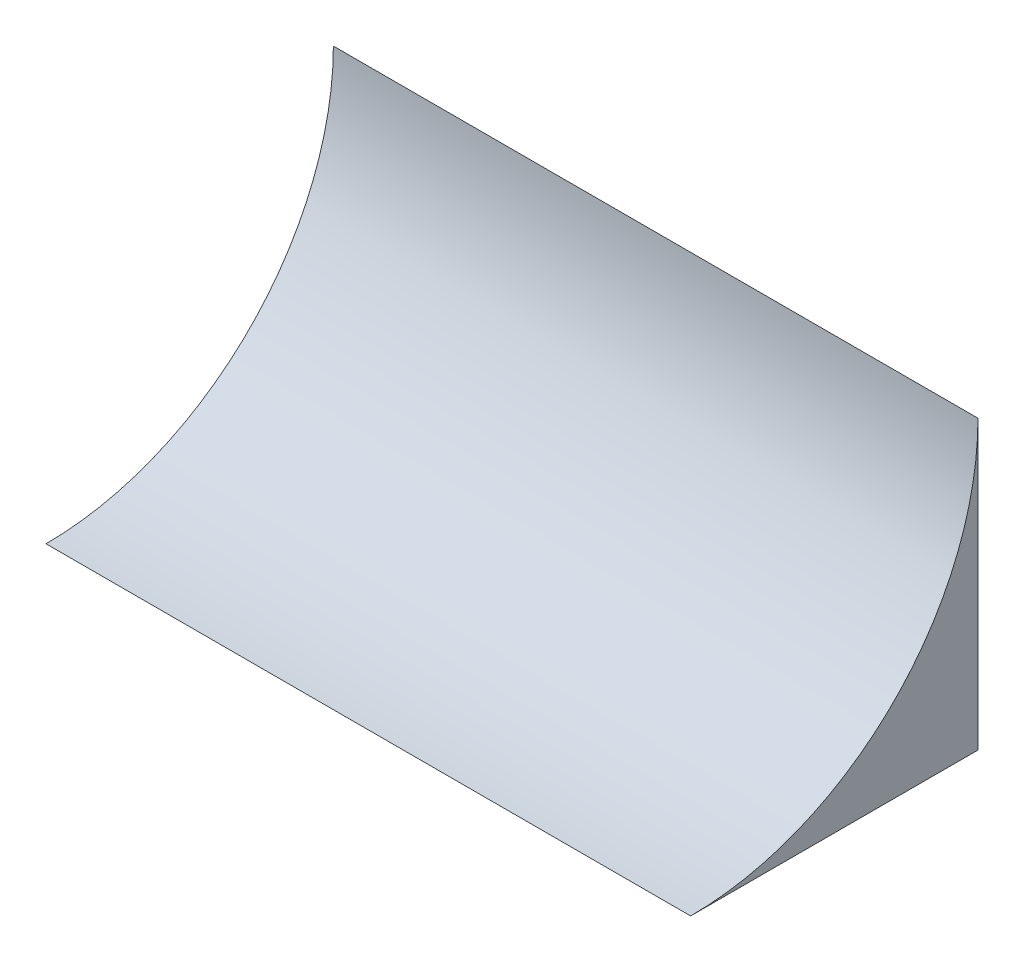
SolidWorks part; units mm, degrees
ref_plane "Front Plane" through (0, 0, 0) normal (0, 0, 1) x (1, 0, 0)
ref_plane "Top Plane" through (0, 0, 0) normal (0, 1, 0) x (1, 0, 0)
ref_plane "Right Plane" through (0, 0, 0) normal (1, 0, 0) x (0, 0, -1)
sketch "Sketch1" plane through (0, 0, 0) normal (1, 0, 0) x (0, 0, -1)
  line L6 (-22.29, -22.29) -> (22.29, -22.29)
  line L8 (-22.29, -22.29) -> (-22.29, 22.29)
  line L9 (-22.29, 22.29) -> (22.29, 22.29)
  line L10 (22.29, -22.29) -> (22.29, 22.29)
  line L11 (0, 22.29) -> (0, -22.29) construction
  line L12 (-22.29, 0) -> (22.29, 0) construction
  point P0 (0, 0)
  point P1 (0, 0)
  dimension "D1" = 44.58
  dimension "D2" = 44.58
extrude "Boss-Extrude1" add sketch "Sketch1" along normal blind 100
sketch "Sketch2" plane through (100, 0, 0) normal (1, 0, 0) x (0, 0, -1)
  circle A0 centre (-22.29, 22.29) radius 44.58
extrude "Cut-Extrude1" cut sketch "Sketch2" against normal blind 100
